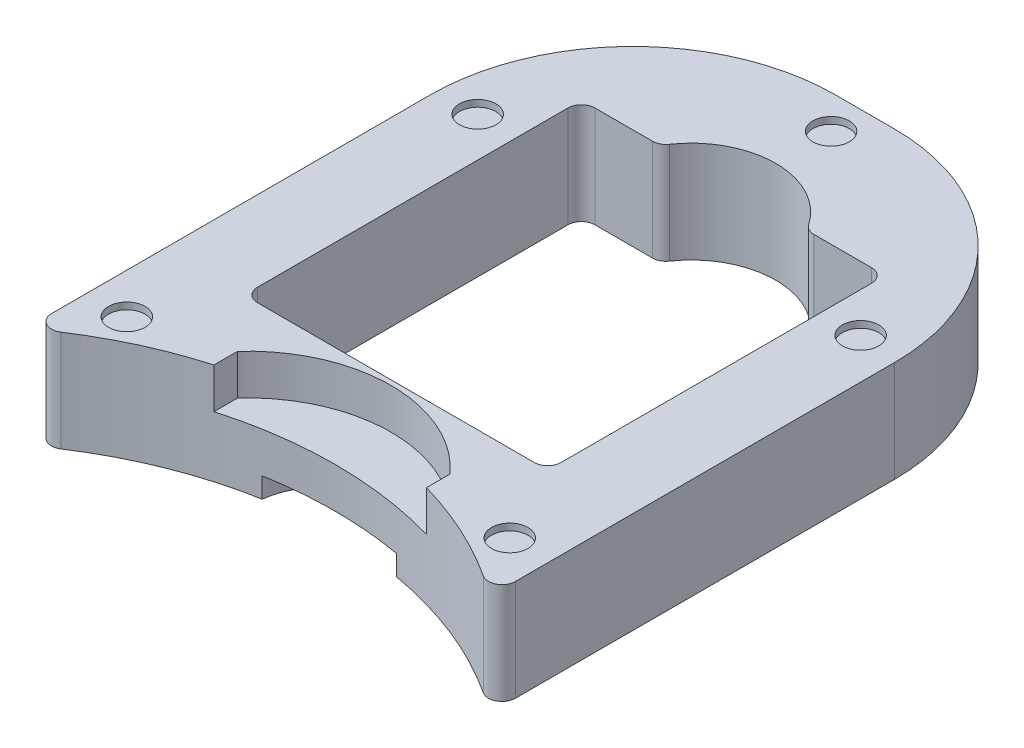
SolidWorks part; units mm, degrees
ref_plane "Front Plane" through (0, 0, 0) normal (0, 0, 1) x (1, 0, 0)
ref_plane "Top Plane" through (0, 0, 0) normal (0, 1, 0) x (1, 0, 0)
ref_plane "Right Plane" through (0, 0, 0) normal (1, 0, 0) x (0, 0, -1)
sketch "Sketch1" plane through (0, 0, 0) normal (0, 1, 0) x (1, 0, 0)
  line L0 (-87.3125, 199.39) -> (-87.3125, -29.21)
  line L1 (-87.3125, 0) -> (87.3125, 0) construction
  line L2 (87.3125, -29.21) -> (87.3125, 199.39)
  line L3 (-87.3125, 199.39) -> (87.3125, 199.39)
  arc A0 (-87.3125, -29.21) -> (87.3125, -29.21) centre (0, -145.0992) cw
  point P9 (0, 0)
  dimension "D1" = 29.21
  dimension "D2" = 174.625
  dimension "D3" = 228.6
extrude "Base" add sketch "Sketch1" along normal blind 38.1
sketch "Sketch2" plane through (0, 0, 0) normal (0, -1, 0) x (-1, 0, 0)
  line L0 (0, 0) -> (0, 199.39) construction
  line L1 (-87.3125, 199.39) -> (87.3125, 199.39) construction
  line L2 (74.549, 108.712) -> (-74.549, 108.712) construction
  line L3 (71.8344, 8.89) -> (-71.8344, 8.89) construction
  line L4 (-43.9941, 159.512) -> (-32.9956, 153.162)
  line L5 (32.9956, 153.162) -> (43.9941, 159.512)
  circle A0 centre (71.8344, 8.89) radius 8.89
  circle A1 centre (74.549, 108.712) radius 10.16
  circle A2 centre (-74.549, 108.712) radius 10.16
  circle A3 centre (-71.8344, 8.89) radius 8.89
  arc A4 (-43.9941, 159.512) -> (43.9941, 159.512) centre (0, 134.112) cw
  arc A5 (-32.9956, 153.162) -> (32.9956, 153.162) centre (0, 134.112) cw
  point P11 (0, 108.712)
  point P14 (0, 8.89)
  point P24 (0, 184.912)
  point P25 (0, 172.212)
  dimension "D1" = 17.78
  dimension "D2" = 20.32
  dimension "D4" = 99.822
  dimension "D3" = 149.098
  dimension "D5" = 143.6687
  dimension "D6" = 38.1
  dimension "D7" = 76.2
  dimension "D8" = 12.7
  dimension "D9" = 25.4
  dimension "D10" = 120
extrude "Coffee Maker Feet Cutouts" cut sketch "Sketch2" against normal blind 2.54
sketch "Sketch10" plane through (0, 0, 0) normal (0, -1, 0) x (-1, 0, 0)
  line L0 (-74.549, 108.712) -> (-74.549, 116.332) construction
  line L1 (-84.709, 108.712) -> (-84.709, 116.332)
  line L2 (-64.389, 108.712) -> (-64.389, 116.332)
  arc A0 (-84.709, 108.712) -> (-64.389, 108.712) centre (-74.549, 108.712) ccw
  arc A1 (-64.389, 116.332) -> (-84.709, 116.332) centre (-74.549, 116.332) ccw
  circle A2 centre (-74.549, 108.712) radius 10.16 construction
  point P3 (-74.549, 112.522)
  dimension "D1" = 7.62
extrude "Asymmetric Foot Slot" cut sketch "Sketch10" against normal up to surface (2.54 mm away) up to face at (74.549, 2.54, -118.872)
sketch "Sketch11" plane through (0, 38.1, 0) normal (0, 1, 0) x (1, 0, 0)
  circle A0 centre (0, -5.08) radius 25.4
  circle A2 centre (-71.8344, 8.89) radius 8.89 construction
  point P2 (0, 20.32)
  point P3 (0, 0)
  dimension "D1" = 50.8
  dimension "D2" = 11.43
extrude "Front cutout" cut sketch "Sketch11" along normal blind 7.62 from surface at -38.1 starting at face at (74.549, 0, -112.522)
fillet "Fillet1" radius 76.2 2 edges at (87.3125, 19.05, -199.39) (-87.3125, 19.05, -199.39)
sketch "Sketch4" plane through (0, 0, 0) normal (0, -1, 0) x (1, 0, 0)
  line L0 (40.005, -3.2662) -> (40.005, 5.6238)
  line L1 (40.005, 5.6238) -> (-40.005, 5.6238)
  line L2 (-40.005, 5.6238) -> (-40.005, -3.2662)
  arc A1 (-87.3125, 29.21) -> (-25.2375, 2.2117) centre (0, 145.0992) ccw construction
  arc A2 (-40.005, -3.2662) -> (40.005, -3.2662) centre (0, 32.8495) ccw
  arc A4 (-87.3125, 29.21) -> (87.3125, 29.21) centre (0, 145.0992) ccw construction
  point P2 (-32.591, 3.7075)
  point P3 (0, -5.2941)
  point P11 (0, -21.0462)
  dimension "D3" = 17.78
  dimension "D1" = 80.01
  dimension "D4" = 8.89
  dimension "D2" = 32.591
extrude "Drip Tray Cutout" cut sketch "Sketch4" along normal blind 15.24 from surface at -38.1 starting at face at (0, 38.1, -107.9188)
sketch "Sketch5" plane through (0, 38.1, 0) normal (0, 1, 0) x (1, 0, 0)
  line L0 (0, 0) -> (0, 204.6816) construction
  line L1 (11.1125, 199.39) -> (-11.1125, 199.39) construction
  line L2 (-87.3125, 123.19) -> (-87.3125, -29.21) construction
  circle A0 centre (-72.0725, -6.35) radius 6.858
  circle A3 centre (-72.0725, 125.73) radius 6.858
  circle A5 centre (0, 186.69) radius 6.858
  circle A6 centre (72.0725, 125.73) radius 6.858
  circle A7 centre (72.0725, -6.35) radius 6.858
  point P4 (0, 0)
  point P9 (67.7736, 18.9879)
  point P12 (-68.3815, 125.0552)
  point P15 (65.9501, 125.0552)
  point P18 (0, 188.2701)
  point P19 (0, 0)
  point P22 (0, 0)
  point P27 (0, 0)
  dimension "D1" = 13.716
  dimension "D2" = 12.7
  dimension "D3" = 15.24
  dimension "D4" = 15.24
  dimension "D5" = 22.86
  dimension "D6" = 132.08
extrude "Feet Pads" cut sketch "Sketch5" against normal blind 2.54
sketch "Sketch6" plane through (0, 0, 0) normal (0, -1, 0) x (-1, 0, 0)
  line L0 (27.5692, 149.86) -> (57.15, 149.86)
  line L1 (-57.15, 149.86) -> (-27.5692, 149.86)
  line L2 (-57.15, 149.86) -> (-57.15, 22.86)
  line L3 (-57.15, 22.86) -> (57.15, 22.86)
  line L4 (57.15, 149.86) -> (57.15, 22.86)
  arc A0 (27.5692, 149.86) -> (-27.5692, 149.86) centre (0, 134.112) ccw
  arc A1 (32.9956, 153.162) -> (-32.9956, 153.162) centre (0, 134.112) ccw construction
  point P4 (0, 22.86)
  point P8 (0, 0)
  dimension "D4" = 63.5
  dimension "D1" = 22.86
  dimension "D2" = 127
  dimension "D3" = 114.3
extrude "Center cutout" cut sketch "Sketch6" against normal through all
fillet "Fillet2" radius 5.08 6 edges at (57.15, 19.05, -22.86) (-57.15, 19.05, -22.86) (57.15, 19.05, -149.86) (27.5692, 19.05, -149.86) (-27.5692, 19.05, -149.86) (-57.15, 19.05, -149.86)
fillet "Fillet4" radius 5.08 2 edges at (87.3125, 19.05, 29.21) (-87.3125, 19.05, 29.21)
sketch "Sketch9" plane through (0, 0, 0) normal (1, 0, 0) x (0, 0, -1)
  line L0 (199.39, 5.08) -> (189.23, 0)
  line L1 (189.23, 0) -> (199.39, 0)
  line L2 (199.39, 0) -> (199.39, 5.08)
  line L3 (149.86, 0) -> (152.0672, 0) construction
  point P2 (0, 0)
  point P6 (0, 0)
  dimension "D1" = 5.08
  dimension "D2" = 10.16
extrude "Easy-Printer-Release-Tab" cut sketch "Sketch9" against normal mid plane 20.32
sketch "Sketch8" plane through (0, 0, 0) normal (0, -1, 0) x (-1, 0, 0)
  line L0 (-72.2313, 83.312) -> (-72.2313, 31.75) construction
  line L1 (-62.23, 83.312) -> (-62.23, 31.75)
  line L2 (-82.2325, 83.312) -> (-82.2325, 31.75)
  line L3 (-87.3125, 83.312) -> (-57.15, 83.312) construction
  line L4 (-87.3125, -19.4345) -> (-87.3125, 123.19) construction
  line L5 (-57.15, 144.78) -> (-57.15, 27.94) construction
  line L6 (0, 0) -> (0, 107.7943) construction
  line L7 (72.2313, 83.312) -> (72.2313, 31.75) construction
  line L10 (62.23, 83.312) -> (62.23, 31.75)
  line L11 (82.2325, 83.312) -> (82.2325, 31.75)
  arc A0 (-62.23, 83.312) -> (-82.2325, 83.312) centre (-72.2313, 83.312) ccw
  arc A1 (-82.2325, 31.75) -> (-62.23, 31.75) centre (-72.2313, 31.75) ccw
  circle A2 centre (-74.549, 108.712) radius 10.16 construction
  circle A3 centre (-71.8344, 8.89) radius 8.89 construction
  circle A6 centre (-43.882, 7.9324) radius 11.43
  circle A9 centre (-58.5568, 166.0702) radius 7.6301
  circle A10 centre (-40.2438, 181.7424) radius 7.145
  circle A11 centre (-20.6916, 191.2716) radius 5.5781
  circle A12 centre (-26.2697, 15.2479) radius 5.5781
  circle A13 centre (-76.3809, -10.8198) radius 6.6198
  arc A16 (62.23, 83.312) -> (82.2325, 83.312) centre (72.2313, 83.312) cw
  arc A17 (82.2325, 31.75) -> (62.23, 31.75) centre (72.2313, 31.75) cw
  circle A18 centre (26.2697, 15.2479) radius 5.5781
  circle A19 centre (43.882, 7.9324) radius 11.43
  circle A20 centre (76.3809, -10.8198) radius 6.6198
  circle A24 centre (58.5568, 166.0702) radius 7.6301
  circle A25 centre (40.2438, 181.7424) radius 7.145
  circle A26 centre (20.6916, 191.2716) radius 5.5781
  circle A27 centre (-72.2313, 142.4454) radius 9.2338
  circle A28 centre (72.2313, 142.4454) radius 7.2636
  point P2 (-72.2313, 57.531)
  point P13 (-72.2313, 83.312)
  point P23 (72.2313, 57.531)
  dimension "D4" = 22.86
  dimension "D1" = 25.4
  dimension "D2" = 22.86
  dimension "D3" = 5.08
extrude "CheeseHole" [suppressed] cut sketch "Sketch8" against normal through all
sketch "Sketch7" plane through (0, 38.1, 0) normal (0, 1, 0) x (1, 0, 0)
  line L0 (-57.15, 27.94) -> (-57.15, 144.78) construction
  line L1 (-57.15, 123.19) -> (-57.15, 37.4168)
  line L2 (-57.15, 37.4168) -> (57.15, 37.4168)
  line L3 (57.15, 144.78) -> (57.15, 27.94) construction
  line L4 (57.15, 37.4168) -> (57.15, 123.19)
  line L5 (-6.35, 173.99) -> (6.35, 173.99)
  arc A0 (-57.15, 123.19) -> (-6.35, 173.99) centre (-6.35, 123.19) cw
  arc A1 (57.15, 123.19) -> (6.35, 173.99) centre (6.35, 123.19) ccw
  circle A2 centre (0, 186.69) radius 6.858 construction
  point P14 (0, 0)
  dimension "D1" = 12.7
  dimension "D2" = 50.8
extrude "Coutout_extra_back" [suppressed] cut sketch "Sketch7" against normal offset from surface (30.48 mm away) 7.62
sketch "Sketch12" plane through (0, 38.1, 0) normal (0, 1, 0) x (1, 0, 0)
  line L1 (-109.7026, 211.2495) -> (117.2164, 211.2495)
  line L2 (-109.7026, 211.2495) -> (-109.7026, -34.8351)
  line L3 (-109.7026, -34.8351) -> (117.2164, -34.8351)
  line L4 (117.2164, 211.2495) -> (117.2164, -34.8351)
extrude "WIP_only_print_top" [suppressed] cut sketch "Sketch12" against normal offset from surface (35.56 mm away) 2.54
sketch "Sketch13" plane through (0, 38.1, 0) normal (0, 1, 0) x (1, 0, 0)
  line L0 (-48.6468, -31.2652) -> (-48.6468, 35.7867)
  line L1 (-48.6468, 35.7867) -> (45.9166, 35.7867)
  line L2 (45.9166, 35.7867) -> (45.9166, -31.2652)
  line L3 (45.9166, -31.2652) -> (112.0431, -31.2652)
  line L4 (112.0431, -31.2652) -> (112.0431, 211.7568)
  line L5 (112.0431, 211.7568) -> (-152.2641, 211.7568)
  line L6 (-152.2641, 211.7568) -> (-152.2641, -31.2652)
  line L7 (-152.2641, -31.2652) -> (-48.6468, -31.2652)
  point P9 (0, 0)
extrude "WIP_only_print_front" [suppressed] cut sketch "Sketch13" against normal through all
